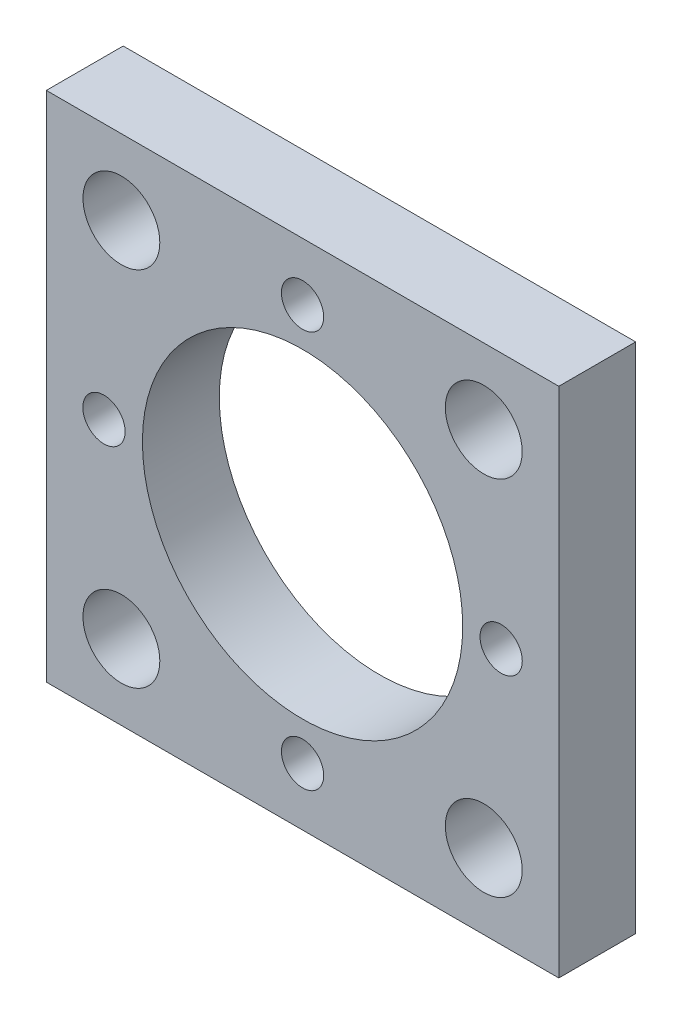
SolidWorks part; units mm, degrees
material "6061-T6 (SS)"
ref_plane "Front Plane" through (0, 0, 0) normal (0, 0, 1) x (1, 0, 0)
ref_plane "Top Plane" through (0, 0, 0) normal (0, 1, 0) x (1, 0, 0)
ref_plane "Right Plane" through (0, 0, 0) normal (1, 0, 0) x (0, 0, -1)
sketch "Sketch1" plane through (0, 0, 0) normal (0, 0, 1) x (1, 0, 0)
  line L1 (0, 0) -> (40, 0)
  line L2 (0, 0) -> (0, 40)
  line L3 (0, 40) -> (40, 40)
  line L4 (40, 0) -> (40, 40)
  dimension "D1" = 40
extrude "Boss-Extrude1" add sketch "Sketch1" along normal blind 6
sketch "Sketch2" plane through (0, 0, 6) normal (0, 0, 1) x (1, 0, 0)
  line L0 (0, 40) -> (40, 0) construction
  line L1 (40, 0) -> (40, 40) construction
  line L2 (40, 40) -> (0, 0) construction
  line L3 (40, 40) -> (0, 0) construction
  line L4 (40, 0) -> (0, 40) construction
  line L5 (0, 0) -> (40, 40) construction
  circle A0 centre (20, 20) radius 20
  point P20 (5.8579, 34.1421)
  point P31 (34.1421, 34.1421)
  point P34 (34.1421, 5.8579)
  point P37 (5.8579, 5.8579)
  dimension "D1" = 4
hole_wizard "Ø6.0mm Dowel Hole1" positions "Sketch2" profile "Sketch4" hole size "Ø6.0" standard "DIN" end condition through all
sketch "Sketch4" plane through (5.8579, 5.8579, 6) normal (1, 0, 0) x (0, -1, 0)
  line L0 (0, 0) -> (0, 6)
  line L1 (0, 6) -> (3, 6)
  line L2 (3, 6) -> (3, 0)
  line L5 (3, 0) -> (0, 0)
  line L11 (0, -6.35) -> (0, 107.95) construction
  dimension "Thru Hole Dia." = 6
  dimension "Thru Hole Depth" = 6
sketch "Sketch5" plane through (0, 0, 6) normal (0, 0, 1) x (1, 0, 0)
  line L0 (0, 40) -> (40, 0) construction
  line L1 (40, 0) -> (40, 40) construction
  line L2 (40, 40) -> (0, 0) construction
  circle A0 centre (20, 20) radius 12.5
  dimension "D1" = 25
extrude "Cut-Extrude1" cut sketch "Sketch5" against normal through all
sketch "Sketch8" plane through (0, 0, 6) normal (0, 0, 1) x (1, 0, 0)
  circle A0 centre (20, 20) radius 15.5
  point P6 (20, 35.5)
  point P13 (35.5, 20)
  point P14 (20, 4.5)
  point P15 (4.5, 20)
  dimension "D1" = 31
hole_wizard "Tap Drill for M4 Tap1" positions "Sketch8" profile "Sketch9" hole size "M4" standard "DIN" end condition through all
sketch "Sketch9" plane through (4.5, 20, 6) normal (1, 0, 0) x (0, -1, 0)
  line L0 (0, 0) -> (0, 6)
  line L1 (0, 6) -> (1.65, 6)
  line L2 (1.65, 6) -> (1.65, 0)
  line L5 (1.65, 0) -> (0, 0)
  line L11 (0, -6.35) -> (0, 107.95) construction
  dimension "Thru Hole Dia." = 3.3
  dimension "Thru Hole Depth" = 6
sketch "Sketch10" [suppressed] plane through (0, 0, 0) normal (-1, 0, 0) x (0, 0, 1)
  line L0 (0, 40) -> (6, 0) construction
  line L1 (6, 0) -> (6, 40) construction
  line L2 (6, 40) -> (0, 0) construction
  line L4 (3, 20) -> (3, 28) construction
  line L6 (3, 20) -> (3, 12) construction
  point P12 (3, 28)
  point P17 (3, 12)
  point P25 (3, 28)
  point P27 (3, 12)
  dimension "D1" = 16
hole_wizard "Tap Drill for M3 Tap1" [suppressed] positions "Sketch10" profile "Sketch11" hole size "M3" standard "DIN"
sketch "Sketch11" plane through (0, 12, 3) normal (0, 1, 0) x (0, 0, 1)
  line L0 (0, 0) -> (0, 40)
  line L1 (0, 40) -> (1.25, 40)
  line L2 (1.25, 40) -> (1.25, 0)
  line L5 (1.25, 0) -> (0, 0)
  line L11 (0, -6.35) -> (0, 107.95) construction
  dimension "Thru Hole Dia." = 2.5
  dimension "Thru Hole Depth" = 40
